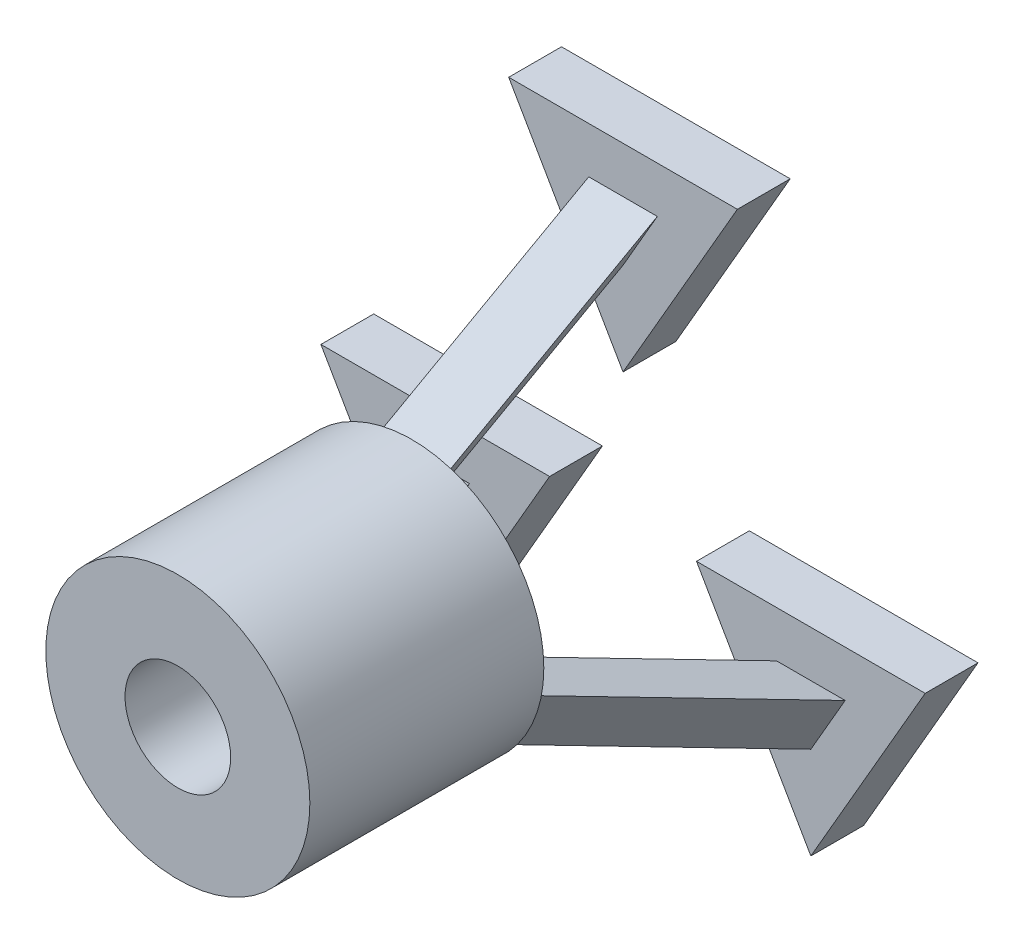
SolidWorks part; units mm, degrees
ref_plane "前视基准面" through (0, 0, 0) normal (0, 0, 1) x (1, 0, 0)
ref_plane "上视基准面" through (0, 0, 0) normal (0, 1, 0) x (1, 0, 0)
ref_plane "右视基准面" through (0, 0, 0) normal (1, 0, 0) x (0, 0, -1)
sketch "草图1" plane through (0, 0, 0) normal (0, 0, 1) x (1, 0, 0)
  circle A0 centre (0, 0) radius 2
  circle A1 centre (0, 0) radius 5
  dimension "D1" = 4
  dimension "D2" = 10
extrude "凸台-拉伸1" add sketch "草图1" along normal blind 8.86
ref_plane "基准面1" through (0, 0, -8) normal (0, 0, 1) x (1, 0, 0)
sketch "草图2" plane through (0, 0, -8) normal (0, 0, 1) x (1, 0, 0)
  line L0 (0, 8.2123) -> (7.1121, -4.1062) construction
  line L1 (0, 6.7123) -> (1.299, 8.9623)
  line L2 (1.299, 8.9623) -> (-1.299, 8.9623)
  line L3 (-1.299, 8.9623) -> (0, 6.7123)
  line L4 (5.9355, -3.1758) -> (6.8947, -5.5903)
  line L5 (6.8947, -5.5903) -> (8.5061, -3.5524)
  line L6 (8.5061, -3.5524) -> (5.9355, -3.1758)
  line L7 (-5.9329, -3.1791) -> (-8.5045, -3.5485)
  line L8 (-8.5045, -3.5485) -> (-6.8988, -5.5909)
  line L9 (-6.8988, -5.5909) -> (-5.9329, -3.1791)
  line L10 (7.1121, -4.1062) -> (-7.1121, -4.1062) construction
  line L11 (-7.1121, -4.1062) -> (0, 8.2123) construction
  line L12 (0, 0) -> (7.1121, -4.1062) construction
  line L13 (0, 0) -> (-7.1121, -4.1062) construction
  line L14 (0, 0) -> (0, 8.2123) construction
  circle A0 centre (0, 8.2123) radius 0.75 construction
  circle A1 centre (7.1121, -4.1062) radius 0.75 construction
  circle A2 centre (-7.1121, -4.1062) radius 0.75 construction
  point P17 (0, -4.1062)
  dimension "D1" = 1.5
  dimension "D2" = 1.5
  dimension "D3" = 1.5
  dimension "D4" = 60
sketch "草图3" plane through (0, 0, 0) normal (0, 0, -1) x (-1, 0, 0)
  line L0 (0, 0) -> (0, 8.2123) construction
  line L1 (0, 2.2528) -> (1.299, 4.5028)
  line L2 (1.299, 4.5028) -> (-1.299, 4.5028)
  line L3 (-1.299, 4.5028) -> (0, 2.2528)
  line L4 (0, 0) -> (-7.1121, -4.1062) construction
  line L5 (-1.951, -1.1264) -> (-4.549, -1.1264)
  line L6 (-4.549, -1.1264) -> (-3.25, -3.3764)
  line L7 (-3.25, -3.3764) -> (-1.951, -1.1264)
  line L8 (0, 0) -> (7.1121, -4.1062) construction
  line L9 (1.951, -1.1264) -> (3.25, -3.3764)
  line L10 (3.25, -3.3764) -> (4.549, -1.1264)
  line L11 (4.549, -1.1264) -> (1.951, -1.1264)
  line L12 (0, 3.7528) -> (-3.25, -1.8764) construction
  line L13 (-3.25, -1.8764) -> (3.25, -1.8764) construction
  line L14 (3.25, -1.8764) -> (0, 3.7528) construction
  circle A0 centre (0, 3.7528) radius 0.75 construction
  circle A1 centre (-3.25, -1.8764) radius 0.75 construction
  circle A2 centre (3.25, -1.8764) radius 0.75 construction
  point P21 (0, 3.8985)
  dimension "D1" = 1.5
  dimension "D2" = 1.5
  dimension "D3" = 1.5
  dimension "D4" = 60
  dimension "D5" = 6.5
loft "放样1" add section "草图3" section "草图2"
pattern_circular "阵列(圆周)1" count 3 over 360 about axis through (0, 0, 0) along (0, 0, 1) of "放样1"
sketch "草图4" plane through (0, 0, -8) normal (0, 0, -1) x (-1, 0, 0)
  line L0 (-1.299, 8.9623) -> (0.6495, 7.8373) construction
  line L1 (1.299, 8.9623) -> (0, 6.7123) construction
  line L2 (1.299, 8.9623) -> (-0.6495, 7.8373) construction
  line L3 (0, 6.7123) -> (-1.299, 8.9623) construction
  line L5 (0, 3.2123) -> (4.3301, 10.7123)
  line L6 (4.3301, 10.7123) -> (-4.3301, 10.7123)
  line L7 (-4.3301, 10.7123) -> (0, 3.2123)
  circle A0 centre (0, 8.2123) radius 2.5 construction
  point P10 (0, 8.2123)
  dimension "D1" = 5
extrude "凸台-拉伸2" add sketch "草图4" along normal blind 2
pattern_circular "阵列(圆周)2" count 3 every 120 about axis through (0, 0, 0) along (0, 0, 1) of "凸台-拉伸2"
sketch "草图5" plane through (0, 0, 0) normal (0, 0, -1) x (-1, 0, 0)
  circle A0 centre (0, 0) radius 2
extrude "凸台-拉伸3" add sketch "草图5" against normal blind 2 separate body
